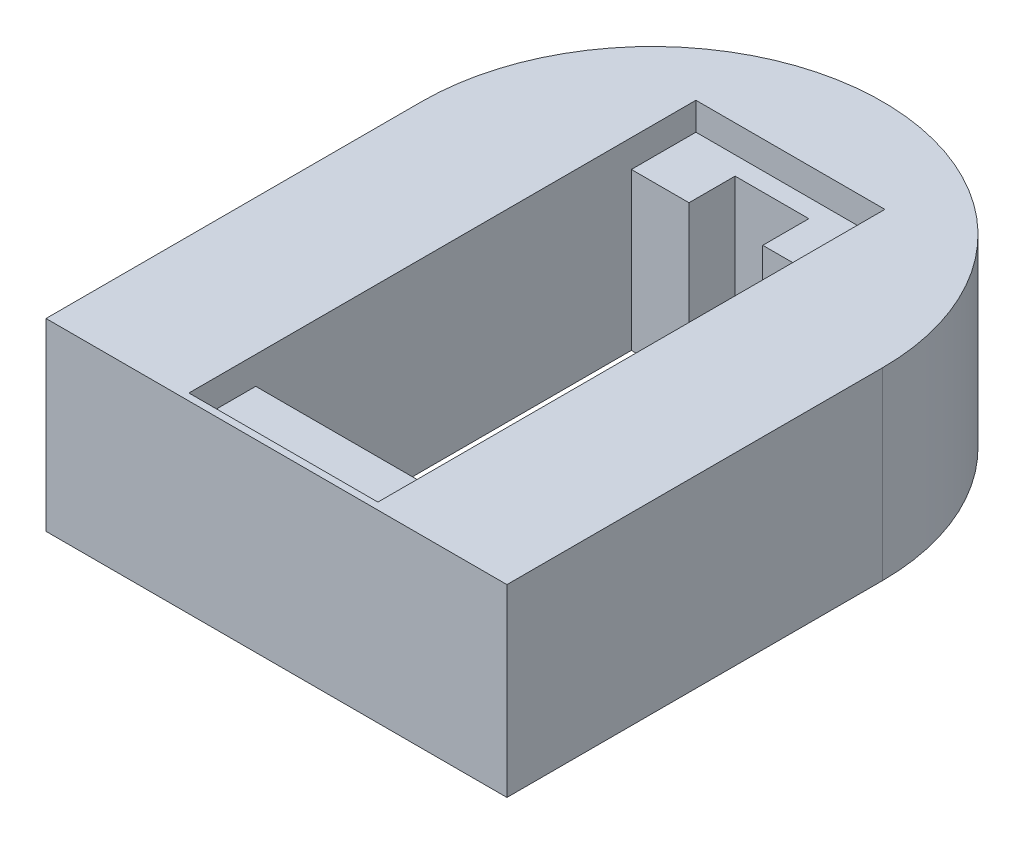
SolidWorks part; units mm, degrees
ref_plane "Front Plane" through (0, 0, 0) normal (0, 0, 1) x (1, 0, 0)
ref_plane "Top Plane" through (0, 0, 0) normal (0, 1, 0) x (1, 0, 0)
ref_plane "Right Plane" through (0, 0, 0) normal (1, 0, 0) x (0, 0, -1)
sketch "Sketch1" plane through (0, 0, 0) normal (0, 1, 0) x (1, 0, 0)
  line L4 (0, 0) -> (50, 0)
  line L5 (50, 0) -> (50, 40.75)
  line L6 (0, 0) -> (0, 40.75)
  arc A0 (0, 40.75) -> (50, 40.75) centre (25, 40.75) cw
  point P12 (0, 0)
  dimension "D5" = 40.75
  dimension "D4" = 50
extrude "Boss-Extrude1" add sketch "Sketch1" along normal blind 20 contours A0 L5 L4 L6
sketch "Sketch2" plane through (0, 20, 0) normal (0, 1, 0) x (1, 0, 0)
  line L0 (14.75, 8) -> (35.25, 8)
  line L1 (35.25, 8) -> (35.25, 48.75)
  line L3 (14.75, 48.75) -> (14.75, 8)
  line L4 (0, 0) -> (50, 0) construction
  line L5 (14.75, 48.75) -> (21, 48.75)
  line L6 (21, 48.75) -> (21, 53.75)
  line L7 (21, 53.75) -> (29, 53.75)
  line L8 (29, 53.75) -> (29, 48.75)
  line L9 (29, 48.75) -> (35.25, 48.75)
  point P6 (25, 8)
  point P7 (25, 0)
  point P10 (32.125, 48.75)
  dimension "D1" = 20.5
  dimension "D2" = 40.75
  dimension "D3" = 8
  dimension "D4" = 5
  dimension "D5" = 8
extrude "Cut-Extrude1" cut sketch "Sketch2" against normal blind 20
sketch "Sketch3" plane through (0, 20, 0) normal (0, 1, 0) x (1, 0, 0)
  line L0 (14.75, 48.75) -> (14.75, 55.75)
  line L1 (14.75, 55.75) -> (35.25, 55.75)
  line L2 (35.25, 55.75) -> (35.25, 48.75)
  line L4 (14.75, 8) -> (14.75, 0.75)
  line L5 (14.75, 0.75) -> (35.25, 0.75)
  line L6 (35.25, 0.75) -> (35.25, 8)
  line L7 (14.75, 8) -> (35.25, 8) construction
  line L8 (21, 48.75) -> (14.75, 48.75) construction
  line L9 (14.75, 48.75) -> (35.25, 48.75)
  line L10 (14.75, 8) -> (35.25, 8)
  dimension "D1" = 7.25
  dimension "D2" = 7
extrude "Cut-Extrude2" cut sketch "Sketch3" against normal blind 3
